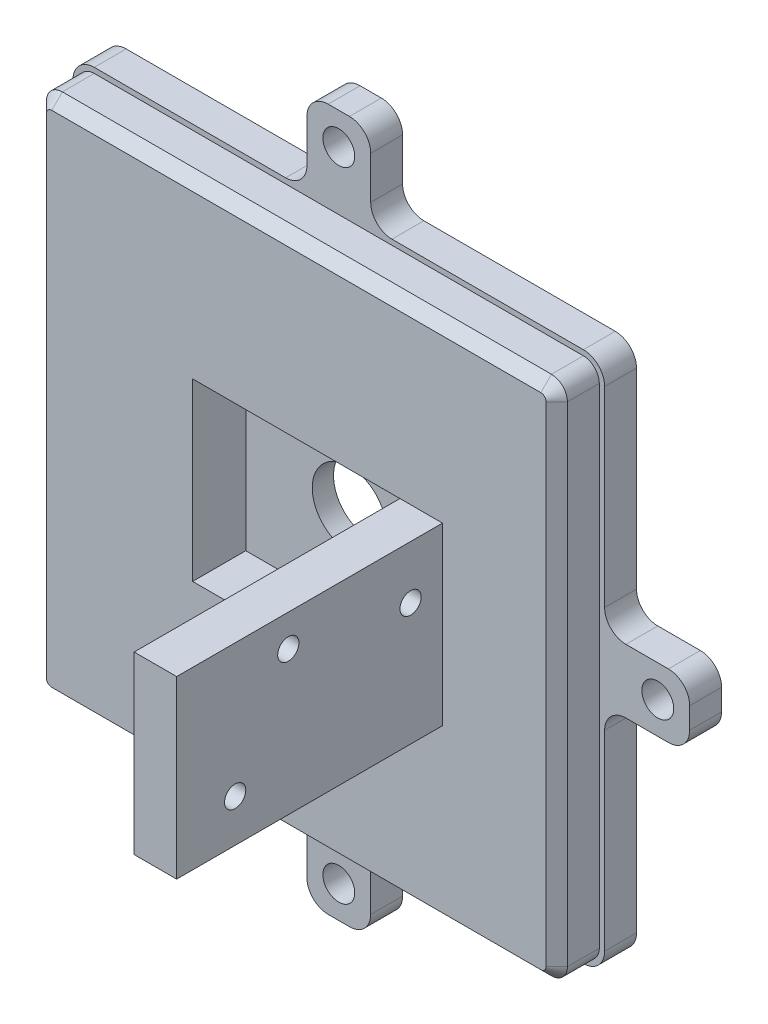
SolidWorks part; units mm, degrees
ref_plane "Front Plane" through (0, 0, 0) normal (0, 0, 1) x (1, 0, 0)
ref_plane "Top Plane" through (0, 0, 0) normal (0, 1, 0) x (1, 0, 0)
ref_plane "Right Plane" through (0, 0, 0) normal (1, 0, 0) x (0, 0, -1)
sketch "Sketch1" plane through (0, 0, 0) normal (0, 0, 1) x (1, 0, 0)
  line L1 (-25, 25) -> (25, 25)
  line L2 (-25, 25) -> (-25, -25)
  line L3 (-25, -25) -> (25, -25)
  line L4 (25, 25) -> (25, -25)
  line L5 (-25, 25) -> (25, -25) construction
  line L6 (-25, -25) -> (25, 25) construction
  point P0 (0, 0)
  dimension "D1" = 50
extrude "Boss-Extrude1" add sketch "Sketch1" along normal blind 7
sketch "Sketch3" plane through (0, 0, 7) normal (0, 0, 1) x (1, 0, 0)
  line L1 (-9.75, 8.25) -> (9.75, 8.25)
  line L2 (-9.75, 8.25) -> (-9.75, -8.25)
  line L3 (-9.75, -8.25) -> (9.75, -8.25)
  line L4 (9.75, 8.25) -> (9.75, -8.25)
  line L5 (-9.75, 8.25) -> (9.75, -8.25) construction
  line L6 (-9.75, -8.25) -> (9.75, 8.25) construction
  point P0 (0, 0)
  dimension "D1" = 16.5
  dimension "D2" = 19.5
extrude "Cut-Extrude1" cut sketch "Sketch3" against normal blind 5
sketch "Sketch4" plane through (0, 0, 2) normal (0, 0, 1) x (1, 0, 0)
  circle A0 centre (0, 0) radius 3.5
  dimension "D1" = 7
extrude "Cut-Extrude2" cut sketch "Sketch4" against normal blind 5
sketch "Sketch5" plane through (0, 0, 7) normal (0, 0, 1) x (1, 0, 0)
  line L0 (-9.75, -8.25) -> (9.75, -8.25) construction
  line L1 (-4, -8.25) -> (4, -8.25)
  arc A0 (4, -8.25) -> (-4, -8.25) centre (0, -8.25) cw
  dimension "D1" = 4
extrude "Cut-Extrude4" cut sketch "Sketch5" against normal through all
sketch "Sketch6" plane through (0, 0, 7) normal (0, 0, 1) x (1, 0, 0)
  line L1 (9.75, -8.25) -> (13.75, -8.25)
  line L2 (9.75, -8.25) -> (9.75, 8.25)
  line L3 (9.75, 8.25) -> (13.75, 8.25)
  line L4 (13.75, -8.25) -> (13.75, 8.25)
  line L5 (9.75, 8.25) -> (-9.75, 8.25) construction
  dimension "D1" = 4
extrude "Boss-Extrude2" add sketch "Sketch6" along normal blind 25
sketch "Sketch7" plane through (13.75, 0, 0) normal (1, 0, 0) x (0, 0, -1)
  line L0 (-7, -25) -> (-7, 25) construction
  line L1 (-32, 8.25) -> (-7, 8.25) construction
  line L2 (-32, -8.25) -> (-32, 8.25) construction
  line L3 (-32, -8.25) -> (-7, -8.25) construction
  circle A0 centre (-10, 3.25) radius 1
  circle A1 centre (-26.5, -4.25) radius 1
  circle A2 centre (-21.5, 5.25) radius 1
  dimension "D3" = 2
  dimension "D4" = 2
  dimension "D7" = 2
  dimension "D9" = 10.5
  dimension "D1" = 3
  dimension "D2" = 5
  dimension "D5" = 5.5
  dimension "D6" = 4
  dimension "D8" = 3
extrude "Cut-Extrude5" cut sketch "Sketch7" against normal through all
sketch "Sketch10" plane through (0, 0, 0) normal (0, 0, -1) x (-1, 0, 0)
  line L0 (-25, 0) -> (25, 0) construction
  line L1 (-25, -25) -> (-25, 25) construction
  line L2 (25, 25) -> (25, -25) construction
  line L3 (3, 25) -> (3, 33)
  line L4 (-25, 3) -> (-33, 3)
  line L5 (-25, 3) -> (-25, -3)
  line L6 (-25, -3) -> (-33, -3)
  line L7 (-33, 3) -> (-33, -3)
  line L8 (3, 25) -> (-3, 25)
  line L9 (-3, 25) -> (-3, 33)
  line L10 (3, 33) -> (-3, 33)
  line L15 (-3, -25) -> (-3, -33)
  line L16 (-3, -25) -> (3, -25)
  line L17 (3, -25) -> (3, -33)
  line L18 (-3, -33) -> (3, -33)
  line L19 (25, -3) -> (33, -3) [skipped]
  line L20 (25, 3) -> (33, 3) [skipped]
  line L21 (33, -3) -> (33, 3) [skipped]
  line L22 (25, -3) -> (25, 3) [skipped]
  circle A0 centre (-30, 0) radius 1.5
  circle A1 centre (0, 30) radius 1.5
  circle A3 centre (0, -30) radius 1.5
  circle A4 centre (30, 0) radius 1.5 [skipped]
  point P10 (-25, 0)
  point P34 (0, 0)
  dimension "D3" = 3
  dimension "D1" = 6
  dimension "D2" = 8
  dimension "D4" = 5
  dimension "D5" = 4
extrude "Boss-Extrude3" add sketch "Sketch10" against normal blind 3
fillet "Fillet1" radius 2 12 edges at (-3, 33, 1.5) (3, 33, 1.5) (33, 3, 1.5) (33, -3, 1.5) (-3, -33, 1.5) (3, -33, 1.5) (3, -25, 1.5) (-3, -25, 1.5) (-3, 25, 1.5) (3, 25, 1.5) (25, -3, 1.5) (25, 3, 1.5)
fillet "Fillet2" radius 2 4 edges at (-25, 25, 3.5) (25, 25, 3.5) (25, -25, 3.5) (-25, -25, 3.5)
sketch "Sketch11" plane through (0, 0, 7) normal (0, 0, 1) x (1, 0, 0)
  line L24 (23, 25) -> (-23, 25)
  line L25 (-25, 23) -> (-25, -23)
  line L26 (-23, -25) -> (23, -25)
  line L27 (25, -23) -> (25, 23)
  line L28 (23, 25) -> (-23, 25)
  line L29 (-25, 23) -> (-25, -23)
  line L30 (-23, -25) -> (23, -25)
  line L31 (25, -23) -> (25, 23)
  line L36 (23, 24.5) -> (-23, 24.5)
  line L37 (-24.5, 23) -> (-24.5, -23)
  line L38 (-23, -24.5) -> (23, -24.5)
  line L39 (24.5, -23) -> (24.5, 23)
  line L40 (23, 24.5) -> (-23, 24.5)
  line L41 (-24.5, 23) -> (-24.5, -23)
  line L42 (-23, -24.5) -> (23, -24.5)
  line L43 (24.5, -23) -> (24.5, 23)
  arc A12 (-23, 25) -> (-25, 23) centre (-23, 23) ccw
  arc A13 (-25, -23) -> (-23, -25) centre (-23, -23) ccw
  arc A14 (23, -25) -> (25, -23) centre (23, -23) ccw
  arc A15 (25, 23) -> (23, 25) centre (23, 23) ccw
  arc A16 (-23, 25) -> (-25, 23) centre (-23, 23) ccw
  arc A17 (-25, -23) -> (-23, -25) centre (-23, -23) ccw
  arc A18 (23, -25) -> (25, -23) centre (23, -23) ccw
  arc A19 (25, 23) -> (23, 25) centre (23, 23) ccw
  arc A24 (-23, 24.5) -> (-24.5, 23) centre (-23, 23) ccw
  arc A25 (-24.5, -23) -> (-23, -24.5) centre (-23, -23) ccw
  arc A26 (23, -24.5) -> (24.5, -23) centre (23, -23) ccw
  arc A27 (24.5, 23) -> (23, 24.5) centre (23, 23) ccw
  arc A28 (-23, 24.5) -> (-24.5, 23) centre (-23, 23) ccw
  arc A29 (-24.5, -23) -> (-23, -24.5) centre (-23, -23) ccw
  arc A30 (23, -24.5) -> (24.5, -23) centre (23, -23) ccw
  arc A31 (24.5, 23) -> (23, 24.5) centre (23, 23) ccw
  dimension "D1" = 0
  dimension "D2" = 0.5
extrude "Cut-Extrude6" cut sketch "Sketch11" against normal up to surface (4 mm away) up to face at (28.5, 0, 3)
chamfer "Chamfer1" distance 1 angle 45 8 edges at (0, 24.5, 7) (-24.5, 0, 7) (0, -24.5, 7) (-24.0607, -24.0607, 7) (-24.0607, 24.0607, 7) (24.0607, -24.0607, 7) (24.0607, 24.0607, 7) (24.5, 0, 7)
